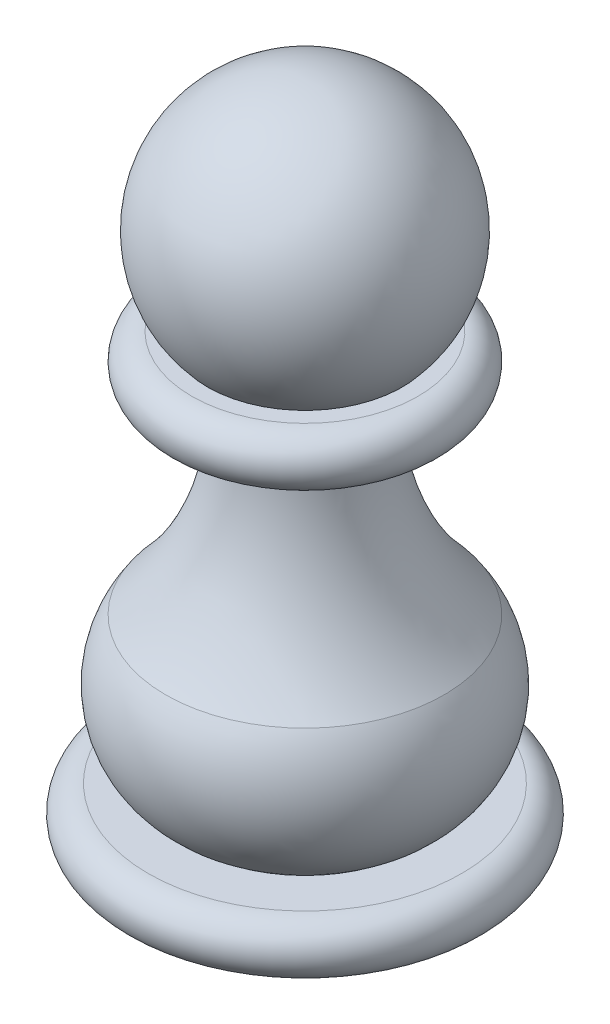
SolidWorks part; units mm, degrees
material "6061 Alloy"
ref_plane "Front Plane" through (0, 0, 0) normal (0, 0, 1) x (1, 0, 0)
ref_plane "Top Plane" through (0, 0, 0) normal (0, 1, 0) x (1, 0, 0)
ref_plane "Right Plane" through (0, 0, 0) normal (1, 0, 0) x (0, 0, -1)
sketch "Pawn Sketch Profile" plane through (0, 0, 0) normal (0, 0, 1) x (1, 0, 0)
  line L0 (0, 16.5059) -> (0, -47.1372) construction
  line L1 (0, -38) -> (-9, -38)
  line L2 (0, -35) -> (-9, -35)
  line L5 (0, -12.5) -> (-6.5, -12.5)
  line L6 (0, -15.5) -> (-6.5, -15.5)
  line L9 (0, 0) -> (0, -38)
  arc A1 (-9, -38) -> (-9, -35) centre (-9, -36.5) cw
  arc A2 (-8, -26.6072) -> (-6.5, -35) centre (-3.0936, -30.0607) ccw
  arc A3 (-6.5, -15.5) -> (-6.5, -12.5) centre (-6.5, -14) cw
  arc A4 (-5.5902, -12.5) -> (0, 0) centre (0, -7.5) cw
  arc A6 (-8, -26.6072) -> (-4, -15.5) centre (-18.9741, -16.3812) ccw
  point P1 (-9, -31.1163)
  dimension "D2" = 1.5
  dimension "D4" = 6
  dimension "D3" = 4
  dimension "D6" = 1.5
  dimension "D7" = 7.5
  dimension "D8" = 12.5
  dimension "D10" = 15
  dimension "D1" = 9
  dimension "D5" = 6.5
  dimension "D9" = 38
  dimension "D11" = 6.5
  dimension "D12" = 9
  dimension "D13" = 8
revolve "Pawn Revolve" add sketch "Pawn Sketch Profile" angle 360 about L0
